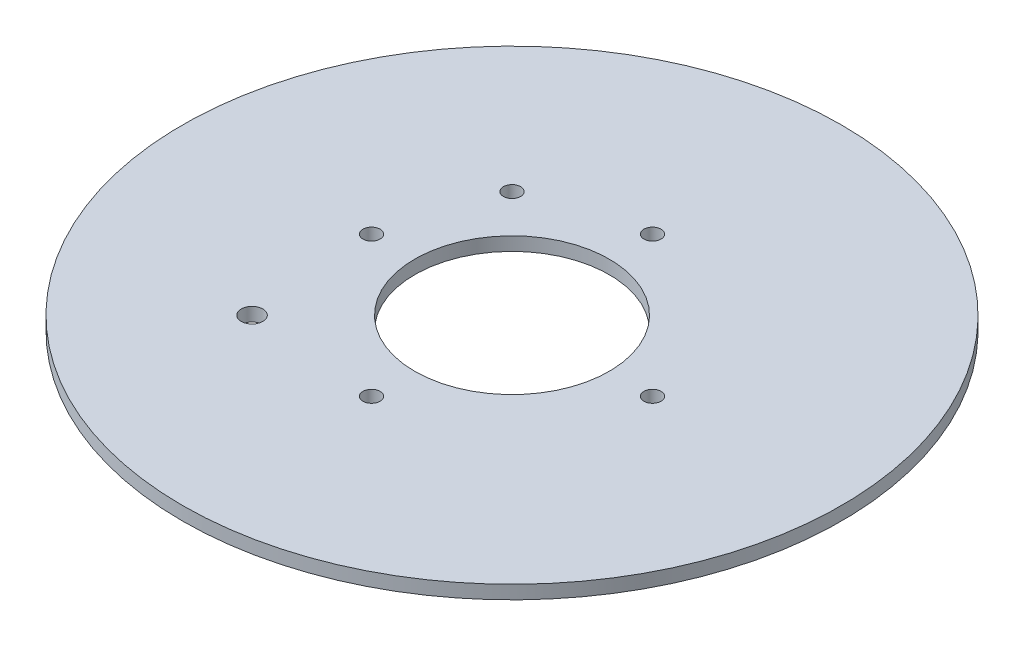
SolidWorks part; units mm, degrees
ref_plane "Front" through (0, 0, 0) normal (0, 0, 1) x (1, 0, 0)
ref_plane "Top" through (0, 0, 0) normal (0, 1, 0) x (1, 0, 0)
ref_plane "Right" through (0, 0, 0) normal (1, 0, 0) x (0, 0, -1)
sketch "Sketch1" plane through (0, 0, 0) normal (0, 1, 0) x (1, 0, 0)
  circle A0 centre (0, 0) radius 77.46
  dimension "D1" = 154.92
extrude "Boss-Extrude1" add sketch "Sketch1" along normal blind 3.175
sketch "Sketch2" plane through (0, 3.175, 0) normal (0, 1, 0) x (1, 0, 0)
  circle A0 centre (0, 0) radius 22.86
  dimension "D1" = 45.72
extrude "Cut-Extrude1" [suppressed] cut sketch "Sketch2" against normal through all
hole_wizard "M3 Clearance Hole1" [suppressed] positions "Sketch4" profile "Sketch3" hole size "M3" standard "ANSI Metric"
sketch "Sketch4" plane through (0, 3.175, 0) normal (0, 1, 0) x (1, 0, 0)
  circle A0 centre (0, 0) radius 27 construction
  point P0 (-27, 0)
  point P2 (0, 27)
  point P4 (27, 0)
  point P6 (0, -27)
  dimension "D1" = 54
sketch "Sketch3" plane through (-27, 3.175, 0) normal (1, 0, 0) x (0, 0, 1)
  line L0 (0, 0) -> (0, 3.175)
  line L1 (0, 3.175) -> (1.7, 3.175)
  line L2 (1.7, 3.175) -> (1.7, 0)
  line L5 (1.7, 0) -> (0, 0)
  line L11 (0, -6.35) -> (0, 107.95) construction
  dimension "Thru Hole Dia." = 3.4
  dimension "Thru Hole Depth" = 3.175
sketch "Sketch5" plane through (0, 0, 0) normal (0, -1, 0) x (-1, 0, 0)
  line L0 (0, 0) -> (116.3694, 0) construction
  line L1 (76.4147, 28.5) -> (66.4147, 28.5)
  line L2 (76.4147, 28.5) -> (76.4147, 31.5)
  line L3 (76.4147, 31.5) -> (66.4147, 31.5)
  line L4 (66.4147, 28.5) -> (66.4147, 31.5)
  line L5 (76.4147, 28.5) -> (66.4147, 31.5) construction
  line L6 (76.4147, 31.5) -> (66.4147, 28.5) construction
  line L7 (76.4147, -28.5) -> (76.4147, -31.5)
  line L8 (76.4147, -28.5) -> (66.4147, -28.5)
  line L9 (66.4147, -28.5) -> (66.4147, -31.5)
  line L10 (76.4147, -31.5) -> (66.4147, -31.5)
  circle A0 centre (0, 0) radius 77.46 construction
  point P0 (71.4147, 30)
  dimension "D1" = 3
  dimension "D2" = 10
  dimension "D3" = 30
extrude "Cut-Extrude2" [suppressed] cut sketch "Sketch5" against normal through all
hole_wizard "M3 Clearance Slot1" [suppressed] positions "Sketch7" profile "Sketch8" size "M3" standard "ANSI Metric"
sketch "Sketch7" plane through (0, 0, 0) normal (0, -1, 0) x (-1, 0, 0)
  line L0 (0, 0) -> (71.3755, 0) construction
  line L1 (55, -30) -> (25, -30) construction
  point P0 (40, -30)
  dimension "D1" = 40
  dimension "D2" = 30
  dimension "D3" = 30
sketch "Sketch8" plane through (-40, 0, 30) normal (1, 0, 0) x (0, 0, -1)
  line L0 (0, 0) -> (0, 26.4215)
  line L1 (0, 26.4215) -> (1.7, 25.4)
  line L2 (1.7, 25.4) -> (1.7, 0)
  line L5 (1.7, 0) -> (0, 0)
  line L10 (0, 26.4215) -> (-1.7, 25.4) construction
  line L11 (0, -6.35) -> (0, 107.95) construction
  dimension "Hole Dia." = 3.4
  dimension "Hole Depth" = 25.4
  dimension "Drill Angle" = 118
hole_wizard "M3 Clearance Hole2" [suppressed] positions "Sketch11" profile "Sketch12" hole size "M3" standard "ANSI Metric"
sketch "Sketch11" [suppressed] plane through (0, 3.175, 0) normal (0, 1, 0) x (1, 0, 0)
  line L0 (-53.3, -28.3) -> (-53.3, 14.1687) construction
  point P0 (-53.3, 30)
  dimension "D1" = 30
sketch "Sketch12" plane through (-53.3, 3.175, -30) normal (1, 0, 0) x (0, 0, 1)
  line L0 (0, 0) -> (0, 3.175)
  line L1 (0, 3.175) -> (1.7, 3.175)
  line L2 (1.7, 3.175) -> (1.7, 0)
  line L5 (1.7, 0) -> (0, 0)
  line L11 (0, -6.35) -> (0, 107.95) construction
  dimension "Thru Hole Dia." = 3.4
  dimension "Thru Hole Depth" = 3.175
sketch "Sketch13" [suppressed] plane through (0, 3.175, 0) normal (0, 1, 0) x (1, 0, 0)
  line L0 (0, 0) -> (0, 33.02) construction
  circle A0 centre (0, 0) radius 33.02 construction
  circle A1 centre (0, 0) radius 22.86 construction
  circle A2 centre (0, 33.02) radius 2.0193
  circle A3 centre (33.02, 0) radius 2.0193
  circle A4 centre (0, -33.02) radius 2.0193
  circle A5 centre (-33.02, 0) radius 2.0193
  point P16 (0, 0)
  dimension "D1" = 10.16
  dimension "D2" = 4.0386
  dimension "D3" = 4
extrude "Cut-Extrude3" [suppressed] cut sketch "Sketch13" against normal up to next
extrude "Cut-Extrude9" [suppressed] cut sketch "Sketch19" against normal through all
sketch "Sketch19" plane through (-73.7688, 25.4, -121.0804) normal (0, 1, 0) x (1, 0, 0)
  circle A1 centre (48.605, -95.9166) radius 2.0193 construction
  circle A3 centre (73.7688, -121.0804) radius 22.86 construction
  circle A4 centre (73.7688, -121.0804) radius 35.587 construction
  arc A5 (40.7129, -134.2614) -> (42.8303, -138.6656) centre (73.7688, -121.0804) ccw construction
  arc A6 (33.7184, -137.0504) -> (36.2838, -142.3866) centre (73.7688, -121.0804) ccw
  arc A7 (47.7074, -131.4723) -> (49.3768, -134.9446) centre (73.7688, -121.0804) ccw
  arc A8 (47.7074, -131.4723) -> (33.7184, -137.0504) centre (40.7129, -134.2614) ccw
  arc A9 (36.2838, -142.3866) -> (49.3768, -134.9446) centre (42.8303, -138.6656) ccw
  point P9 (41.6959, -136.4999)
extrude "Cut-Extrude10" cut sketch "Sketch20" against normal through all
sketch "Sketch20" plane through (-73.7688, 25.4, -121.0804) normal (0, 1, 0) x (1, 0, 0)
  line L0 (73.7688, -121.0804) -> (73.7688, -88.0604) construction
  circle A1 centre (73.7688, -121.0804) radius 77.46 construction
  circle A2 centre (73.7688, -121.0804) radius 22.86
  circle A3 centre (73.7688, -88.0604) radius 2.0193
  circle A4 centre (106.7888, -121.0804) radius 2.0193
  circle A5 centre (73.7688, -154.1004) radius 2.0193
  circle A6 centre (40.7488, -121.0804) radius 2.0193
  point P4 (73.7688, -98.2204)
  point P16 (73.7688, -121.0804)
extrude "Cut-Extrude11" cut sketch "Sketch21" against normal through all
sketch "Sketch21" plane through (-73.7688, 25.4, -121.0804) normal (0, 1, 0) x (1, 0, 0)
  line L0 (43.2169, -90.5284) -> (48.605, -95.9166) construction
  arc A1 (41.4208, -92.3245) -> (45.0129, -88.7324) centre (43.2169, -90.5284) ccw construction
  circle A2 centre (48.605, -95.9166) radius 2.0193
extrude "Cut-Extrude12" [suppressed] cut sketch "Sketch22" against normal through all
sketch "Sketch22" plane through (-73.7688, 25.4, -121.0804) normal (0, 1, 0) x (1, 0, 0)
  circle A2 centre (73.7688, -121.0804) radius 22.86 construction
  circle A3 centre (48.605, -95.9166) radius 2.0193 construction
  circle A4 centre (73.7688, -121.0804) radius 35.587 construction
  arc A5 (40.5263, -133.7834) -> (43.5223, -139.8309) centre (73.7688, -121.0804) ccw construction
  arc A6 (34.406, -136.1222) -> (37.9536, -143.283) centre (73.7688, -121.0804) ccw
  arc A7 (46.6466, -131.4446) -> (49.091, -136.3787) centre (73.7688, -121.0804) ccw
  arc A8 (46.6466, -131.4446) -> (34.406, -136.1222) centre (40.5263, -133.7834) ccw
  arc A9 (37.9536, -143.283) -> (49.091, -136.3787) centre (43.5223, -139.8309) ccw
  point P9 (41.8806, -136.8783)
extrude "Cut-Extrude13" cut sketch "Sketch23" against normal blind 3.175
sketch "Sketch23" plane through (-73.7688, 0, -121.0804) normal (0, -1, 0) x (1, 0, 0)
  arc A1 (41.4208, 149.8362) -> (45.0129, 153.4284) centre (43.2169, 151.6323) ccw construction
  circle A2 centre (43.2169, 151.6323) radius 2.54
